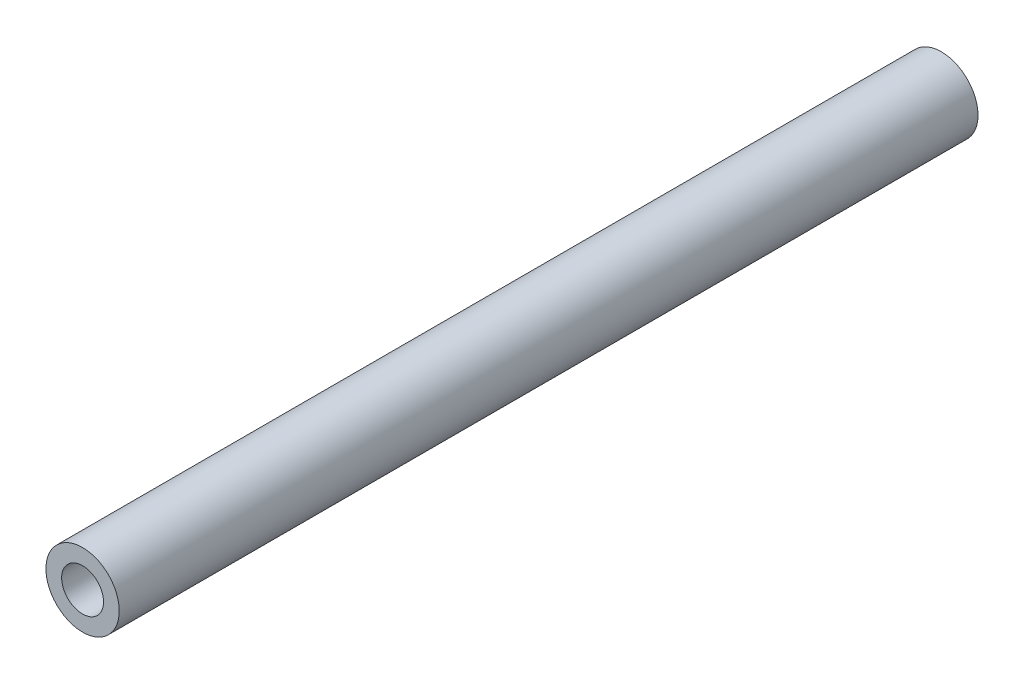
SolidWorks part; units mm, degrees
material "6061 Alloy"
ref_plane "Front Plane" through (0, 0, 0) normal (0, 0, 1) x (1, 0, 0)
ref_plane "Top Plane" through (0, 0, 0) normal (0, 1, 0) x (1, 0, 0)
ref_plane "Right Plane" through (0, 0, 0) normal (1, 0, 0) x (0, 0, -1)
sketch "Sketch1" plane through (0, 0, 0) normal (0, 0, 1) x (1, 0, 0)
  circle A0 centre (-15.9821, 183.9592) radius 2
  circle A1 centre (-15.9821, 183.9592) radius 3.5
  dimension "D1" = 4
  dimension "D2" = 7
extrude "Boss-Extrude1" add sketch "Sketch1" along normal blind 82
